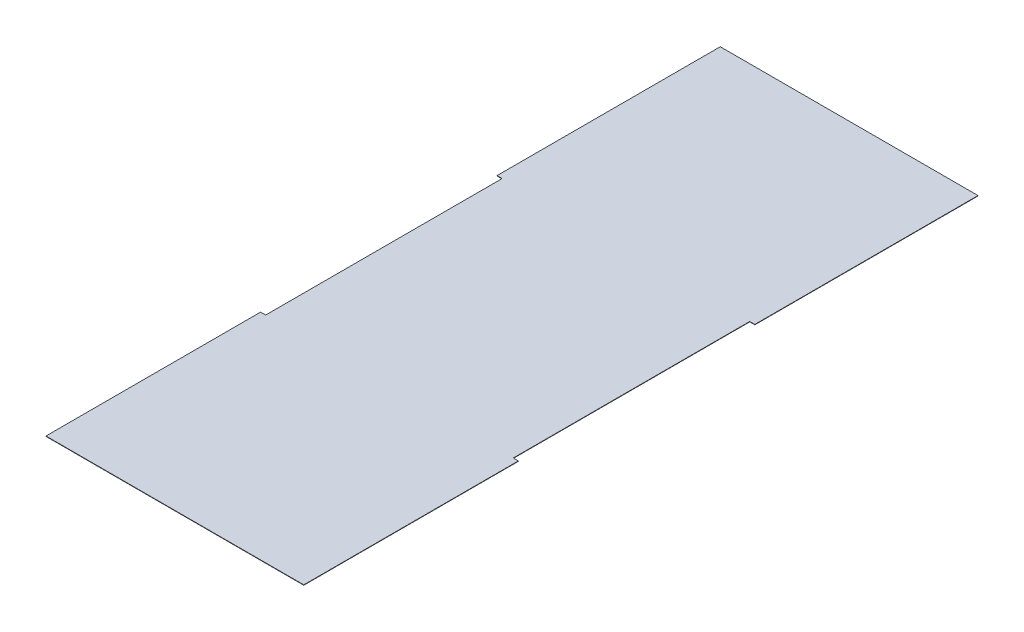
SolidWorks part; units mm, degrees
ref_plane "Front Plane" through (0, 0, 0) normal (0, 0, 1) x (1, 0, 0)
ref_plane "Top Plane" through (0, 0, 0) normal (0, 1, 0) x (1, 0, 0)
ref_plane "Right Plane" through (0, 0, 0) normal (1, 0, 0) x (0, 0, -1)
sketch "Sketch1" plane through (0, 0, 0) normal (0, 1, 0) x (1, 0, 0)
  line L0 (0, 0) -> (0, 5030)
  line L1 (0, 5030) -> (1923, 5030)
  line L2 (1923, 5030) -> (1923, 0)
  line L3 (1923, 0) -> (0, 0)
  dimension "D1" = 1923
  dimension "D2" = 5030
extrude "Boss-Extrude1" add sketch "Sketch1" along normal blind 3
sketch "Sketch2" plane through (0, 3, 0) normal (0, 1, 0) x (1, 0, 0)
  line L0 (0, 1601) -> (38, 1601)
  line L1 (0, 5030) -> (0, 0) construction
  line L2 (38, 1601) -> (38, 3365)
  line L3 (38, 3365) -> (0, 3365)
  line L4 (0, 3365) -> (0, 1601)
  line L5 (1923, 3365) -> (1885, 3365)
  line L6 (1923, 0) -> (1923, 5030) construction
  line L7 (1885, 3365) -> (1885, 1601)
  line L8 (1885, 1601) -> (1923, 1601)
  line L9 (1923, 1601) -> (1923, 3365)
  line L11 (1923, 5030) -> (0, 5030) construction
  dimension "D1" = 38
  dimension "D2" = 38
  dimension "D3" = 1764
  dimension "D4" = 1764
  dimension "D5" = 1665
  dimension "D6" = 1665
extrude "Cut-Extrude1" cut sketch "Sketch2" against normal blind 3
equation "\"MetalSheet_3mm_length\"=5030.0"
equation "\"D2@Sketch1\"=\"MetalSheet_3mm_length\""
equation "\"MetalSheet_3mm_width\"=1923.0"
equation "\"D1@Sketch1\"=\"MetalSheet_3mm_width\""
equation "\"MetalSheet_3mm_FloorCut_L_length\"=1764.0"
equation "\"D3@Sketch2\"= \"MetalSheet_3mm_FloorCut_L_length\""
equation "\"MetalSheet_3mm_FloorCut_L_disdance\"=1665.0"
equation "\"D6@Sketch2\"=\"MetalSheet_3mm_FloorCut_L_disdance\""
equation "\"MetalSheet_3mm_FloorCut_R_length\"=1764.0"
equation "\"D4@Sketch2\"=\"MetalSheet_3mm_FloorCut_R_length\""
equation "\"MetalSheet_3mm_FloorCut_R_disdance\"=1665.0"
equation "\"D5@Sketch2\"=\"MetalSheet_3mm_FloorCut_R_disdance\""
equation "\"indoorHeight\"=1940.0"
equation "\"x\"=66.0"
equation "\"da\"=62.0"
equation "\"SquareTube_length\"=1923.0"
equation "\"CarBeamWidth\"=700.0"
equation "\"SquareTube_wheel_length\"= 750"
equation "\"channelSteel_length\"=5030.0"
equation "\"SquareTube_inFront1_cutDepth50_R\"=0.5"
equation "\"SquareTube_inFront1_cutDepth50_L\"=0.5"
equation "\"SquareTube_inFront2_cutDepth50_R\"=0.5"
equation "\"SquareTube_inFront2_cutDepth50_L\"=0.5"
equation "\"SquareTube_inFront3_cutDepth50_R\"=0.5"
equation "\"SquareTube_inFront3_cutDepth50_L\"=0.5"
equation "\"SquareTube_inFront4_cutDepth50_R\"=0.5"
equation "\"SquareTube_inFront4_cutDepth50_L\"=0.5"
equation "\"SquareTube_inFront5_cutDepth50_R\"=50"
equation "\"SquareTube_inFront5_cutDepth50_L\"=50"
equation "\"SquareTube_inFront6_cutDepth50_R\"=50"
equation "\"SquareTube_inFront6_cutDepth50_L\"=50"
equation "\"SquareTube_inFront7_cutDepth50_R\"=50"
equation "\"SquareTube_inFront7_cutDepth50_L\"=50"
equation "\"SquareTube_inFront8_cutDepth50_R\"=50"
equation "\"SquareTube_inFront8_cutDepth50_L\"=50"
equation "\"SquareTube_inFront9_cutDepth50_R\"=50"
equation "\"SquareTube_inFront9_cutDepth50_L\"=50"
equation "\"SquareTube_inFront10_cutDepth50_R\"=50"
equation "\"SquareTube_inFront10_cutDepth50_L\"=50"
equation "\"SquareTube_inBack1_cutDepth50_R\"=50"
equation "\"SquareTube_inBack1_cutDepth50_L\"=50"
equation "\"SquareTube_inBack2_cutDepth50_R\"=50"
equation "\"SquareTube_inBack2_cutDepth50_L\"=50"
equation "\"SquareTube_inBack3_cutDepth50_R\"=50"
equation "\"SquareTube_inBack3_cutDepth50_L\"=50"
equation "\"SquareTube_inBack4_cutDepth50_R\"=50"
equation "\"SquareTube_inBack4_cutDepth50_L\"=50"
equation "\"SquareTube_inBack5_cutDepth50_R\"=50"
equation "\"SquareTube_inBack5_cutDepth50_L\"=50"
equation "\"SquareTube_inBack6_cutDepth50_R\"=0.5"
equation "\"SquareTube_inBack6_cutDepth50_L\"=0.5"
